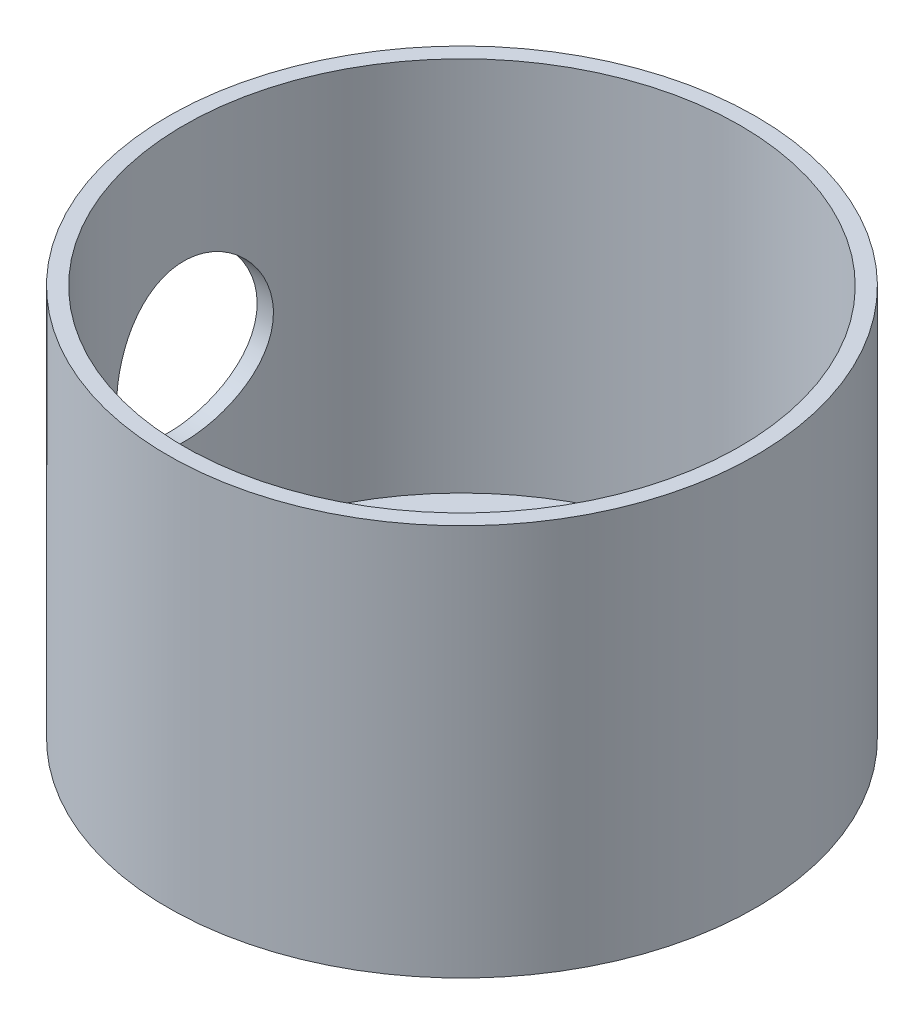
SolidWorks part; units mm, degrees
material "1060 Alloy"
ref_plane "Front Plane" through (0, 0, 0) normal (0, 0, 1) x (1, 0, 0)
ref_plane "Top Plane" through (0, 0, 0) normal (0, 1, 0) x (1, 0, 0)
ref_plane "Right Plane" through (0, 0, 0) normal (1, 0, 0) x (0, 0, -1)
sketch "Sketch1" plane through (0, 0, 0) normal (0, 0, 1) x (1, 0, 0)
  line L0 (20, 17.7) -> (-20, 17.7) construction
  line L1 (-15, 17.7) -> (15, 17.7) construction
  line L2 (-15, 17.7) -> (-15, 37.7)
  line L3 (-15, 37.7) -> (-14.2, 37.7)
  line L4 (15, 17.7) -> (15, 37.7) construction
  line L5 (0, 0) -> (0, 46.558) construction
  line L6 (14.2, 37.7) -> (15, 37.7) construction
  line L7 (0, 18.5) -> (0, 17.7)
  line L8 (-14.2, 37.7) -> (-14.2, 18.5)
  line L9 (-14.2, 18.5) -> (14.2, 18.5) construction
  line L10 (14.2, 37.7) -> (14.2, 18.5) construction
  line L11 (-14.2, 18.5) -> (0, 18.5)
  line L12 (-15, 17.7) -> (0, 17.7)
  dimension "D1" = 30
  dimension "D2" = 20
  dimension "D3" = 0.8
  dimension "D4" = 0.8
revolve "Revolve1" add sketch "Sketch1" angle 360 about L5
sketch "Sketch2" plane through (0, 18.5, 0) normal (0, 1, 0) x (1, 0, 0)
  circle A0 centre (0, 0) radius 4
  dimension "D1" = 8
extrude "Cut-Extrude1" cut sketch "Sketch2" against normal blind 10
sketch "Sketch3" plane through (0, 0, 0) normal (1, 0, 0) x (0, 0, -1)
  line L0 (0, 37.7) -> (0, 17.7) construction
  line L1 (15, 37.7) -> (-15, 37.7) construction
  line L2 (-15, 17.7) -> (15, 17.7) construction
  circle A0 centre (0, 27.7) radius 4
  dimension "D1" = 8
extrude "Cut-Extrude2" cut sketch "Sketch3" against normal blind 18
